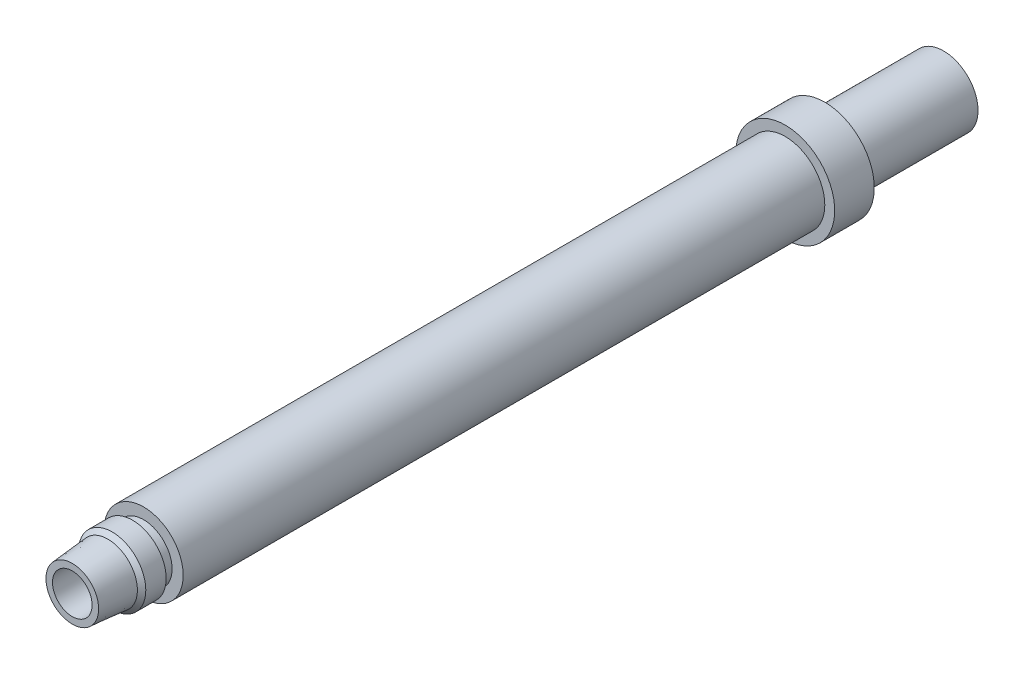
SolidWorks part; units mm, degrees
material "Copper"
ref_plane "Front Plane" through (0, 0, 0) normal (0, 0, 1) x (1, 0, 0)
ref_plane "Top Plane" through (0, 0, 0) normal (0, 1, 0) x (1, 0, 0)
ref_plane "Right Plane" through (0, 0, 0) normal (1, 0, 0) x (0, 0, -1)
sketch "Sketch2" plane through (0, 0, 0) normal (0, 0, 1) x (1, 0, 0)
  circle A0 centre (0, 0) radius 7.9375
  circle A1 centre (0, 0) radius 3.175
  dimension "D1" = 15.875
  dimension "D2" = 6.35
extrude "Boss-Extrude1" add sketch "Sketch2" along normal blind 139.7
sketch "Sketch3" plane through (0, 0, 0) normal (0, 0, -1) x (-1, 0, 0)
  circle A0 centre (0, 0) radius 5.5245
  dimension "D1" = 11.049
extrude "Cut-Extrude1" cut sketch "Sketch3" against normal blind 19.05 flip side to cut
sketch "Sketch4" plane through (0, 0, 139.7) normal (0, 0, 1) x (1, 0, 0)
  circle A0 centre (0, 0) radius 6.35
  dimension "D1" = 12.7
extrude "Cut-Extrude2" cut sketch "Sketch4" against normal offset from surface (114.3 mm away) 6.35 flip side to cut up to face at (-5.5245, 0, 19.05)
sketch "Sketch9" plane through (0, 0, 0) normal (1, 0, 0) x (0, 0, -1)
  line L0 (-139.7, 0) -> (-128.27, 0) construction
  line L1 (-139.7, 6.35) -> (-139.7, -6.35) construction
  line L2 (-128.27, 0) -> (-128.27, 5.3975) construction
  line L3 (-128.27, 5.3975) -> (-133.985, 5.3975) construction
  line L4 (-139.7, 4.7244) -> (-133.985, 4.7244) construction
  line L5 (-133.985, 4.7244) -> (-139.7, 4.2244)
  line L6 (-128.27, 4.572) -> (-130.048, 4.572)
  line L7 (-130.048, 4.572) -> (-130.048, 5.3975)
  line L8 (-133.985, 4.7244) -> (-133.3119, 5.3975)
  line L9 (-133.3119, 5.3975) -> (-130.048, 5.3975)
  line L10 (-128.27, 4.572) -> (-128.27, 6.35)
  line L11 (-25.4, 6.35) -> (-139.7, 6.35) construction
  line L12 (-139.7, 4.2244) -> (-139.7, 6.35)
  line L13 (-139.7, 6.35) -> (-128.27, 6.35)
  dimension "D1" = 11.43
  dimension "D2" = 5.3975
  dimension "D3" = 5.715
  dimension "D4" = 4.7244
  dimension "D5" = 5
  dimension "D6" = 4.572
  dimension "D7" = 45
  dimension "D8" = 1.778
revolve "Cut-Revolve1" cut sketch "Sketch9" angle 360 about L0
